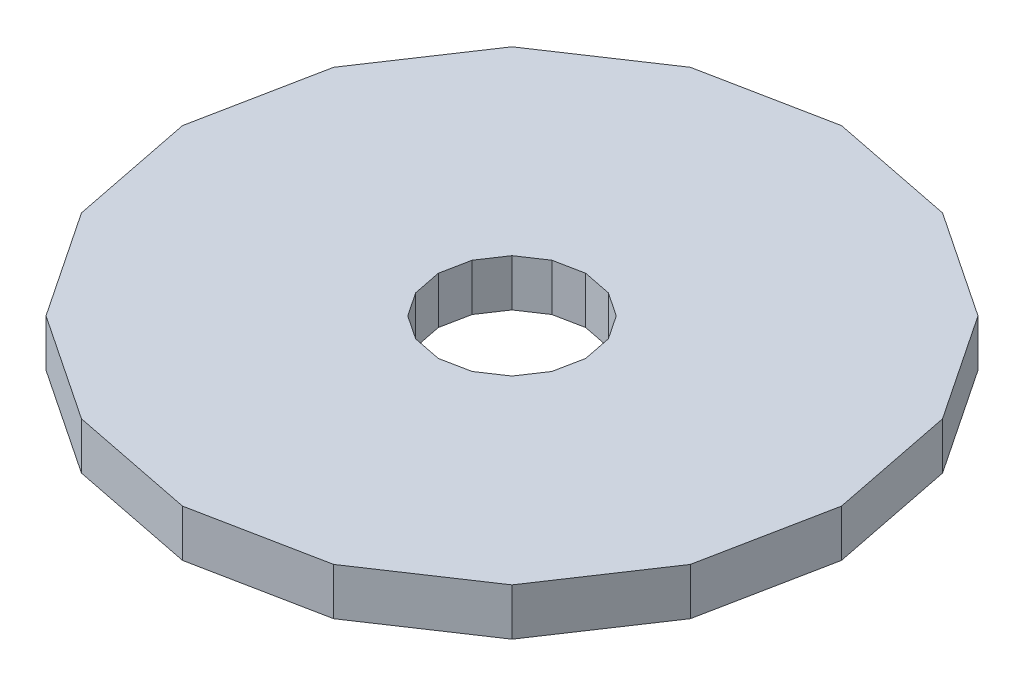
SolidWorks part; units mm, degrees
ref_plane "Front Plane" through (0, 0, 0) normal (0, 0, 1) x (1, 0, 0)
ref_plane "Top Plane" through (0, 0, 0) normal (0, 1, 0) x (1, 0, 0)
ref_plane "Right Plane" through (0, 0, 0) normal (1, 0, 0) x (0, 0, -1)
sketch "Sketch1" plane through (0, 0, 0) normal (0, 1, 0) x (1, 0, 0)
  line L1 (29.8605, 0) -> (27.5875, 11.4271)
  line L2 (27.5875, 11.4271) -> (21.1146, 21.1146)
  line L3 (21.1146, 21.1146) -> (11.4271, 27.5875)
  line L4 (11.4271, 27.5875) -> (0, 29.8605)
  line L5 (0, 29.8605) -> (-11.4271, 27.5875)
  line L6 (-11.4271, 27.5875) -> (-21.1146, 21.1146)
  line L7 (-21.1146, 21.1146) -> (-27.5875, 11.4271)
  line L8 (-27.5875, 11.4271) -> (-29.8605, 0)
  line L9 (-29.8605, 0) -> (-27.5875, -11.4271)
  line L10 (-27.5875, -11.4271) -> (-21.1146, -21.1146)
  line L11 (-21.1146, -21.1146) -> (-11.4271, -27.5875)
  line L12 (-11.4271, -27.5875) -> (0, -29.8605)
  line L13 (0, -29.8605) -> (11.4271, -27.5875)
  line L14 (11.4271, -27.5875) -> (21.1146, -21.1146)
  line L15 (21.1146, -21.1146) -> (27.5875, -11.4271)
  line L16 (27.5875, -11.4271) -> (29.8605, 0)
  line L17 (133.451, 0) -> (123.2927, 51.0695)
  line L18 (123.2927, 51.0695) -> (94.3641, 94.3641)
  line L19 (94.3641, 94.3641) -> (51.0695, 123.2927)
  line L20 (51.0695, 123.2927) -> (0, 133.451)
  line L21 (0, 133.451) -> (-51.0695, 123.2927)
  line L22 (-51.0695, 123.2927) -> (-94.3641, 94.3641)
  line L23 (-94.3641, 94.3641) -> (-123.2927, 51.0695)
  line L24 (-123.2927, 51.0695) -> (-133.451, 0)
  line L25 (-133.451, 0) -> (-123.2927, -51.0695)
  line L26 (-123.2927, -51.0695) -> (-94.3641, -94.3641)
  line L27 (-94.3641, -94.3641) -> (-51.0695, -123.2927)
  line L28 (-51.0695, -123.2927) -> (0, -133.451)
  line L29 (0, -133.451) -> (51.0695, -123.2927)
  line L30 (51.0695, -123.2927) -> (94.3641, -94.3641)
  line L31 (94.3641, -94.3641) -> (123.2927, -51.0695)
  line L32 (123.2927, -51.0695) -> (133.451, 0)
  circle A0 centre (0, 0) radius 29.2868 construction
  circle A1 centre (0, 0) radius 130.8868 construction
  dimension "D1" = 52.07
  dimension "D2" = 101.6
extrude "Boss-Extrude1" add sketch "Sketch1" along normal blind 19.05
